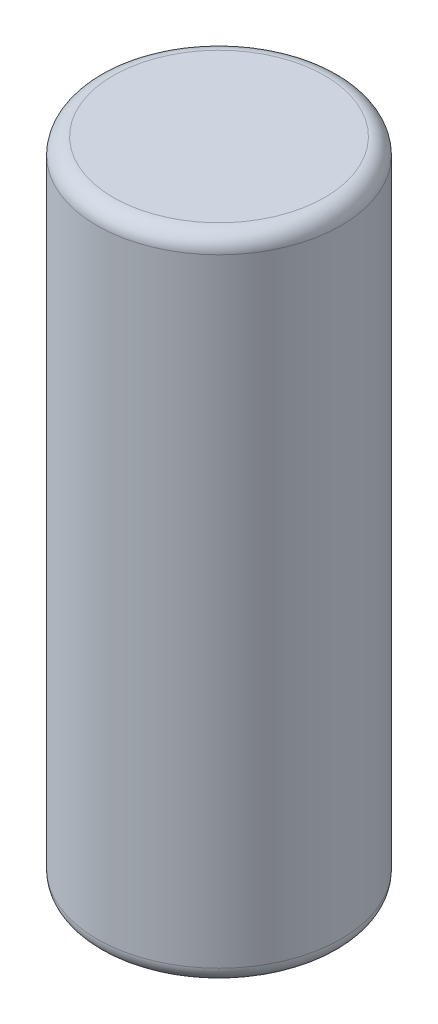
SolidWorks part; units mm, degrees
material "Plain Carbon Steel"
ref_plane "Front Plane" through (0, 0, 0) normal (0, 0, 1) x (1, 0, 0)
ref_plane "Top Plane" through (0, 0, 0) normal (0, 1, 0) x (1, 0, 0)
ref_plane "Right Plane" through (0, 0, 0) normal (1, 0, 0) x (0, 0, -1)
sketch "Sketch1" plane through (0, 0, 0) normal (0, 1, 0) x (1, 0, 0)
  circle A0 centre (0, 0) radius 75
  dimension "D1" = 150
extrude "Boss-Extrude1" add sketch "Sketch1" along normal blind 400
fillet "Fillet1" radius 10 1 edges at (0, 400, 75)
fillet "Fillet2" radius 10 1 edges at (0, 0, 75)
ref_plane "Plane1" through (0, 0, 90) normal (0, 0, 1) x (1, 0, 0)
